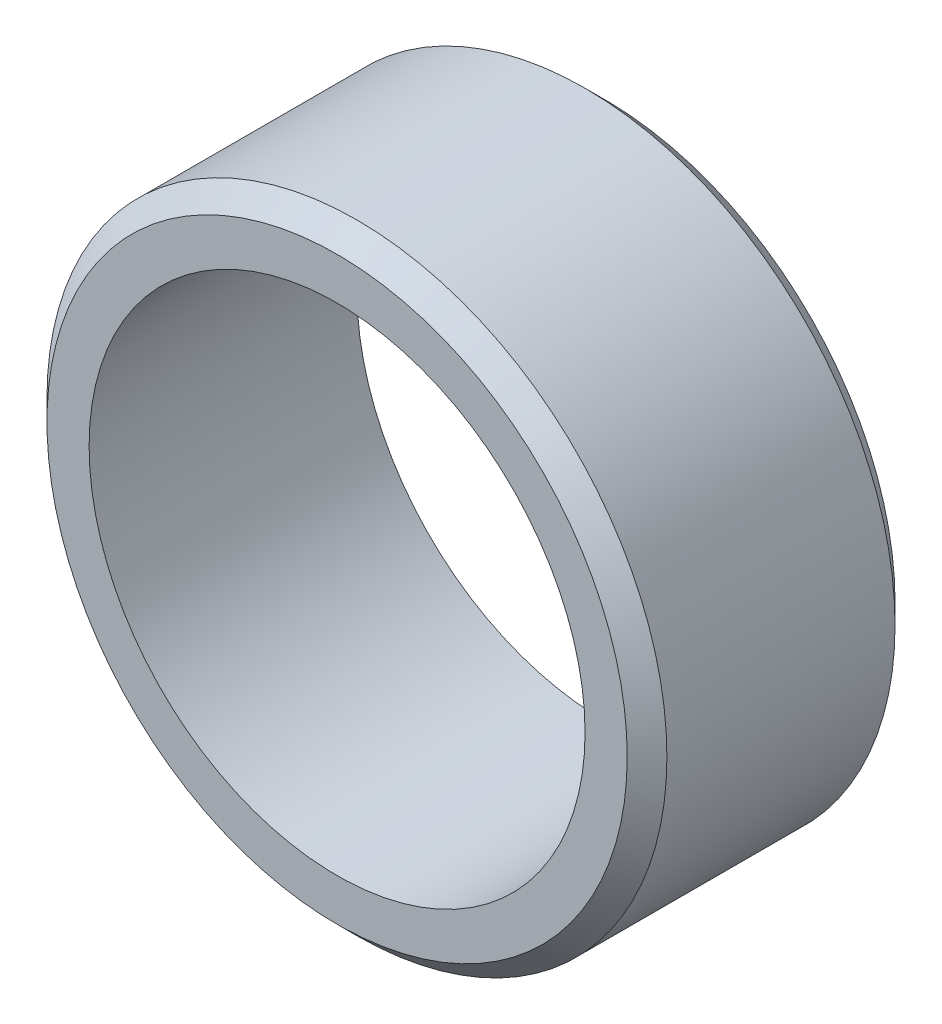
SolidWorks part; units mm, degrees
material "6061-T6 (SS)"
ref_plane "Front Plane" through (0, 0, 0) normal (0, 0, 1) x (1, 0, 0)
ref_plane "Top Plane" through (0, 0, 0) normal (0, 1, 0) x (1, 0, 0)
ref_plane "Right Plane" through (0, 0, 0) normal (1, 0, 0) x (0, 0, -1)
sketch "Sketch1" plane through (0, 0, 0) normal (0, 0, 1) x (1, 0, 0)
  circle A0 centre (0, 0) radius 6.35
  circle A1 centre (0, 0) radius 7.9375
  dimension "D1" = 12.7
  dimension "D2" = 15.875
extrude "Boss-Extrude1" add sketch "Sketch1" along normal blind 6.858
chamfer "Chamfer1" distance 0.508 angle 45 2 edges at (7.9375, 0, 0) (7.9375, 0, 6.858)
